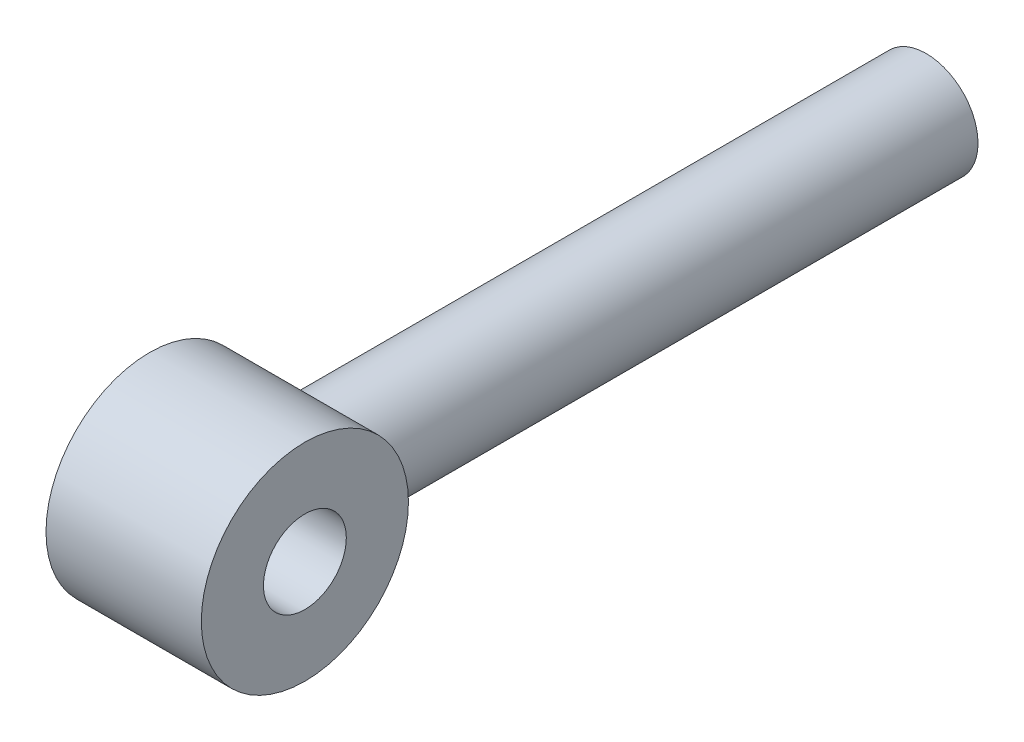
SolidWorks part; units mm, degrees
ref_plane "Front Plane" through (0, 0, 0) normal (0, 0, 1) x (1, 0, 0)
ref_plane "Top Plane" through (0, 0, 0) normal (0, 1, 0) x (1, 0, 0)
ref_plane "Right Plane" through (0, 0, 0) normal (1, 0, 0) x (0, 0, -1)
sketch "Shaft Section" plane through (0, 0, 0) normal (0, 1, 0) x (1, 0, 0)
  line L0 (0, 27) -> (2, 27)
  line L1 (2, 27) -> (2, 3)
  line L2 (2, 3) -> (0, 3)
  line L3 (0, 3) -> (0, 27)
  line L4 (0, -10.123) -> (0, 10.123) construction
  dimension "D1" = 2
  dimension "D2" = 27
  dimension "D3" = 3
  dimension "D4" = 10.123
  dimension "D5" = 10.123
revolve "Rod Revolve" add sketch "Shaft Section" angle 360 about L4
sketch "Eye Sketch" plane through (0, 0, 0) normal (1, 0, 0) x (0, 0, -1)
  circle A0 centre (0, 0) radius 4
  dimension "D1" = 8
extrude "Eye Extrude" add sketch "Eye Sketch" along normal mid plane 6
sketch "Eye Bore Sketch" plane through (0, 0, 0) normal (1, 0, 0) x (0, 0, -1)
  circle A0 centre (0, 0) radius 1.6
  dimension "D1" = 3.2
extrude "Eye Bore Cut" cut sketch "Eye Bore Sketch" against normal mid plane 6
equation "\"eye_diameter\"= 8mm 'Mock shock eye outside diameter"
equation "\"eye_width\"= 6mm 'Eye width along hinge axis X"
equation "\"eye_bore\"= 3.2mm 'M3 hinge clearance"
equation "\"rod_diameter\"= 4mm 'Sliding rod diameter"
equation "\"rod_end_distance\"= 27mm 'Rod tip distance from moving eye"
equation "\"neck_start\"= 3mm 'Neck junction inside eye"
equation "\"axis_reference_halfspan\"= 10.123mm 'Half display length of the construction axis; avoids sharing a profile endpoint"
equation "\"D1@Shaft Section\"= \"rod_diameter\" / 2"
equation "\"D2@Shaft Section\"= \"rod_end_distance\""
equation "\"D3@Shaft Section\"= \"neck_start\""
equation "\"D4@Shaft Section\"= \"axis_reference_halfspan\""
equation "\"D5@Shaft Section\"= \"axis_reference_halfspan\""
equation "\"full_turn\"= 360deg 'Full circular extent for revolves and patterns"
equation "\"D1@Rod Revolve\"= \"full_turn\""
equation "\"D1@Eye Sketch\"= \"eye_diameter\""
equation "\"D1@Eye Extrude\"= \"eye_width\""
equation "\"D1@Eye Bore Sketch\"= \"eye_bore\""
equation "\"D1@Eye Bore Cut\"= \"eye_width\""
